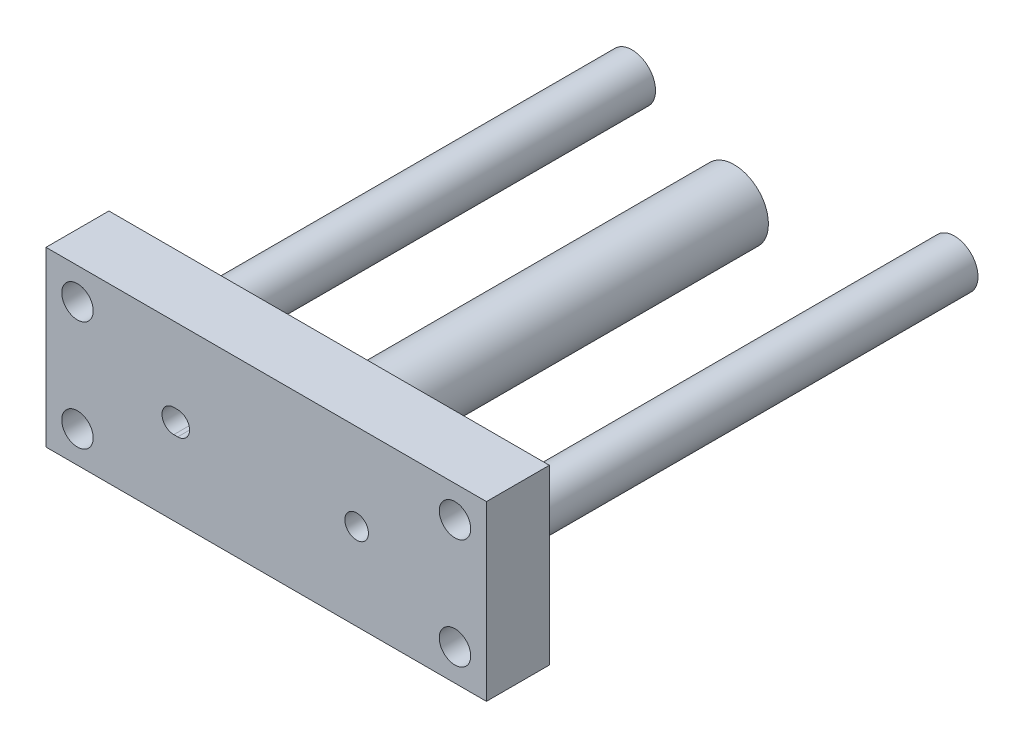
SolidWorks part; units mm, degrees
ref_plane "前视基准面" through (0, 0, 0) normal (0, 0, 1) x (1, 0, 0)
ref_plane "上视基准面" through (0, 0, 0) normal (0, 1, 0) x (1, 0, 0)
ref_plane "右视基准面" through (0, 0, 0) normal (1, 0, 0) x (0, 0, -1)
sketch "草图1" plane through (0, 0, 0) normal (0, 1, 0) x (1, 0, 0)
  line L0 (0, 0) -> (0, 54) construction
  line L1 (-29, 54) -> (29, 54)
  line L2 (-29, 54) -> (-29, 0)
  line L3 (-29, 0) -> (29, 0)
  line L4 (29, 54) -> (29, 0)
  line L5 (-11.5, 0) -> (-11.5, 54) construction
  line L6 (18, 54) -> (18, 0) construction
  line L7 (4.35, 0) -> (4.35, -5)
  line L8 (-29, -5) -> (29, -5)
  line L9 (-29, -5) -> (-29, -13)
  line L10 (-29, -13) -> (29, -13)
  line L11 (29, -5) -> (29, -13)
  line L12 (29, 0) -> (71, 0)
  circle A0 centre (18, 46.5) radius 2.5
  point P4 (29, 25)
  point P8 (0, 25)
  point P11 (-11.5, 5)
  point P12 (-11.5, 25)
  point P15 (18, 46.5)
  point P16 (18, 11)
  point P19 (29, 11)
  point P20 (29, 13.5)
  point P21 (29, 38.5)
  point P28 (0, 51)
  point P29 (0, 48)
  point P30 (-11.5, 15)
  point P31 (18, 54)
  point P33 (-11.5, 44)
  dimension "D2" = 38.5
  dimension "P" = 5
  dimension "D1" = 54
  dimension "B" = 58
  dimension "AC" = 29
  dimension "行程" = 25
  dimension "KB" = 23
  dimension "MB" = 5
  dimension "MC" = 20
  dimension "PB" = 18
  dimension "PD" = 11
  dimension "PF" = 7.5
  dimension "PC" = 11
  dimension "PE" = 13.5
  dimension "D3" = 8.7
  dimension "AD" = 8
  dimension "AB" = 13
  dimension "D4" = 67
  dimension "JA" = 3
  dimension "KA" = 6
  dimension "KC" = 15
  dimension "A" = 42
  dimension "LA" = 10
sketch "草图2" plane through (0, 0, 0) normal (0, 0, 1) x (1, 0, 0)
  line L0 (-29, 0) -> (0, 0) construction
  line L1 (-29, 13) -> (29, 13)
  line L2 (-29, 13) -> (-29, -13)
  line L3 (-29, -13) -> (-20.75, -13)
  line L4 (29, 13) -> (29, -13)
  line L5 (-29, 0) -> (29, 0) construction
  line L6 (0, 0) -> (0, 13) construction
  line L7 (-11.5, 13) -> (-11.5, -13) construction
  line L8 (-7.5, 13) -> (-7.5, 8.5)
  line L9 (-7.5, 8.5) -> (-9.25, 8.5)
  line L10 (-9.25, 8.5) -> (-9.25, -13)
  line L11 (29, 8) -> (24, 8)
  line L12 (-29, 0) -> (29, 0) construction
  line L13 (-11.75, 0) -> (-11.25, 0) construction
  line L14 (-11.75, 1.5) -> (-11.25, 1.5)
  line L15 (-11.75, -1.5) -> (-11.25, -1.5)
  line L16 (-9.25, -3) -> (-9, -3)
  line L17 (-2.25, -13) -> (-2.25, -12)
  line L18 (-9, -3) -> (-9, -13)
  line L19 (-4.5, -12) -> (-4.5, -13)
  line L20 (-16.25, -13) -> (-16.25, -11)
  line L21 (-16.25, -11) -> (-14.75, -11)
  line L22 (-14.75, -11) -> (-14.75, -7)
  line L23 (-14.75, -7) -> (-16.25, -7)
  line L24 (-22.25, -7) -> (-22.25, -11)
  line L25 (-22.25, -11) -> (-20.75, -11)
  line L26 (-20.75, -11) -> (-20.75, -13)
  line L27 (-23, 13) -> (-20.6, 10.6)
  line L28 (-20.6, 10.6) -> (-19.1, 10.6)
  line L29 (-19.1, 10.6) -> (-16.7, 13)
  line L36 (-20.75, -7) -> (-22.25, -7)
  line L37 (-20.75, -6.5) -> (-16.25, -6.5)
  line L38 (-20.75, -6.5) -> (-20.75, -7)
  line L39 (-16.25, -13) -> (29, -13)
  line L40 (-16.25, -6.5) -> (-16.25, -7)
  line L41 (-20.75, -13) -> (-16.25, -13) construction
  line L42 (-2.25, -12) -> (-1.25, -12)
  line L43 (-5.5, -10) -> (-1.25, -10)
  line L44 (-5.5, -10) -> (-5.5, -12)
  line L45 (-5.5, -12) -> (-4.5, -12)
  line L46 (-1.25, -10) -> (-1.25, -12)
  circle A0 centre (-20.5, 0) radius 3
  circle A1 centre (20.5, 0) radius 3
  circle A2 centre (-25, 9) radius 2
  circle A3 centre (-25, -9) radius 2
  circle A4 centre (11.5, 0) radius 1.5
  arc A5 (-11.75, 1.5) -> (-11.75, -1.5) centre (-11.75, 0) ccw
  arc A6 (-11.25, -1.5) -> (-11.25, 1.5) centre (-11.25, 0) ccw
  point P48 (-11.5, 0)
  point P52 (-18.5, -13)
  point P64 (-9.75, 0)
  point P65 (-13.25, 0)
  dimension "D1" = 1
  dimension "D" = 6
  dimension "D7" = 10.4
  dimension "L" = 4
  dimension "D10" = 2.4
  dimension "K" = 3
  dimension "C" = 26
  dimension "G" = 41
  dimension "U" = 7.5
  dimension "W" = 4
  dimension "V" = 4.5
  dimension "X" = 2
  dimension "Y" = 6.5
  dimension "S" = 37
  dimension "D2" = 1
  dimension "D3" = 2
  dimension "M" = 8
  dimension "MA" = 4.5
  dimension "N" = 4.5
  dimension "D4" = 2.25
  dimension "D5" = 2
  dimension "D6" = 135
  dimension "LC" = 18
  dimension "LB" = 50
  dimension "D8" = 2
  dimension "D9" = 5
  dimension "PA" = 8
  dimension "J" = 3.5
  dimension "R" = 5
  dimension "RA" = 10
sketch "草图3" plane through (0, 0, 0) normal (0, 0, 1) x (1, 0, 0)
  line L0 (0, 11) -> (0, 0) construction
  line L1 (-28, 11) -> (28, 11)
  line L2 (-28, 11) -> (-28, -11)
  line L3 (-28, -11) -> (28, -11)
  line L4 (28, 11) -> (28, -11)
  line L5 (-29, 0) -> (29, 0) construction
  line L6 (0, 0) -> (0, -11) construction
  line L7 (-29, 0) -> (29, 0) construction
  circle A0 centre (-24, 7) radius 2
  circle A1 centre (-25, 9) radius 2 construction
  dimension "BA" = 56
  dimension "CA" = 22
  dimension "LD" = 48
  dimension "LE" = 14
sketch "草图4" plane through (0, 0, 0) normal (0, 0, 1) x (1, 0, 0)
  line L0 (-14.75, -7) -> (-16.25, -7) construction
  line L1 (-14.75, -11) -> (-14.75, -7) construction
  line L2 (-16.25, -11) -> (-14.75, -11) construction
  line L3 (-16.25, -13) -> (-16.25, -11) construction
  line L4 (-16.25, -13) -> (29, -13) construction
  line L6 (-29, 13) -> (29, 13) construction
  line L7 (-29, 13) -> (-29, -13) construction
  line L8 (-29, -13) -> (-20.75, -13) construction
  line L9 (-20.75, -11) -> (-20.75, -13) construction
  line L10 (-22.25, -11) -> (-20.75, -11) construction
  line L11 (-22.25, -7) -> (-22.25, -11) construction
  line L12 (-20.75, -7) -> (-22.25, -7) construction
  line L13 (-20.75, -6.5) -> (-20.75, -7) construction
  line L14 (-20.75, -6.5) -> (-16.25, -6.5) construction
  line L15 (-16.25, -6.5) -> (-16.25, -7) construction
  line L26 (-23, 13) -> (-20.6, 10.6) construction
  line L27 (-20.6, 10.6) -> (-19.1, 10.6) construction
  line L28 (-19.1, 10.6) -> (-16.7, 13) construction
  line L29 (-14.75, -7) -> (-16.25, -7)
  line L30 (-14.75, -11) -> (-14.75, -7)
  line L31 (-16.25, -11) -> (-14.75, -11)
  line L32 (-16.25, -13) -> (-16.25, -11)
  line L33 (-16.25, -13) -> (0, -13)
  line L35 (-29, 13) -> (-23, 13)
  line L36 (-29, 13) -> (-29, -13)
  line L37 (-29, -13) -> (-20.75, -13)
  line L38 (-20.75, -11) -> (-20.75, -13)
  line L39 (-22.25, -11) -> (-20.75, -11)
  line L40 (-22.25, -7) -> (-22.25, -11)
  line L41 (-20.75, -7) -> (-22.25, -7)
  line L42 (-20.75, -6.5) -> (-20.75, -7)
  line L43 (-20.75, -6.5) -> (-16.25, -6.5)
  line L44 (-16.25, -6.5) -> (-16.25, -7)
  line L45 (0, 13) -> (0, -13)
  line L52 (-16.7, 13) -> (0, 13)
  line L55 (-23, 13) -> (-20.6, 10.6)
  line L56 (-20.6, 10.6) -> (-19.1, 10.6)
  line L57 (-19.1, 10.6) -> (-16.7, 13)
  circle A4 centre (-20.5, 0) radius 3 construction
  circle A5 centre (-20.5, 0) radius 3
extrude "凸台-拉伸1" add sketch "草图4" against normal up to vertex (54 mm away) up to point (0, 0, -54)
sketch "草图5" plane through (0, 0, 0) normal (0, 0, 1) x (1, 0, 0)
  line L0 (-5.5, -12) -> (-4.5, -12) construction
  line L1 (-4.5, -12) -> (-4.5, -13) construction
  line L2 (-5.5, -10) -> (-5.5, -12) construction
  line L3 (-5.5, -10) -> (-1.25, -10) construction
  line L4 (-1.25, -10) -> (-1.25, -12) construction
  line L5 (-2.25, -12) -> (-1.25, -12) construction
  line L6 (-2.25, -13) -> (-2.25, -12) construction
  line L7 (-5.5, -12) -> (-4.5, -12)
  line L8 (-4.5, -12) -> (-4.5, -13)
  line L9 (-5.5, -10) -> (-5.5, -12)
  line L10 (-5.5, -10) -> (-1.25, -10)
  line L11 (-1.25, -10) -> (-1.25, -12)
  line L12 (-2.25, -12) -> (-1.25, -12)
  line L13 (-2.25, -13) -> (-2.25, -12)
  line L14 (-4.5, -13) -> (-2.25, -13)
extrude "切除-拉伸1" cut sketch "草图5" against normal through all
mirror "镜向1" about plane through (0, 0, 0) normal (0, 1, 0) of "切除-拉伸1"
sketch "草图6" plane through (0, 13, 0) normal (0, 1, 0) x (-1, 0, 0)
  circle A0 centre (11.5, -25) radius 4
  circle A1 centre (11.5, -5) radius 4
  point P6 (7.5, -5)
extrude "切除-拉伸2" cut sketch "草图6" against normal up to vertex (4.5 mm away) up to point (-7.5, 8.5, 0)
sketch "草图7" plane through (0, 8.5, 0) normal (0, 1, 0) x (1, 0, 0)
  circle A0 centre (-11.5, 25) radius 2.25
  circle A1 centre (-11.5, 5) radius 2.25
  point P6 (-9.25, 25)
extrude "切除-拉伸3" cut sketch "草图7" against normal up to vertex (21.5 mm away) up to point (-9.25, -13, 0)
mirror "镜向2" about plane through (0, 0, 0) normal (1, 0, 0) of bodies 105
sketch "草图8" plane through (0, 0, 0) normal (0, 0, 1) x (1, 0, 0)
  line L0 (16.7, 13) -> (23, 13)
  line L1 (23, 13) -> (20.6, 10.6)
  line L2 (20.6, 10.6) -> (19.1, 10.6)
  line L3 (19.1, 10.6) -> (16.7, 13)
extrude "凸台-拉伸2" add sketch "草图8" against normal up to surface (54 mm away) up to face at (-17.5, 0, -54)
sketch "草图9" plane through (0, 13, 0) normal (0, 1, 0) x (1, 0, 0)
  circle A0 centre (18, 46.5) radius 2.5
  circle A1 centre (18, 11) radius 2.5
  circle A2 centre (18, 46.5) radius 2.5 construction
extrude "切除-拉伸4" cut sketch "草图9" against normal blind 5
sketch "草图10" plane through (29, 0, 0) normal (1, 0, 0) x (0, 0, -1)
  circle A0 centre (11, 8) radius 2.5
  circle A1 centre (38.5, 8) radius 2.5
  dimension "D1" = 5
extrude "切除-拉伸5" cut sketch "草图10" against normal up to vertex (5 mm away) up to point (24, 8, 0)
sketch "草图11" plane through (0, 0, 0) normal (0, 0, 1) x (1, 0, 0)
  line L0 (-29, 0) -> (29, 0) construction
  circle A0 centre (0, 0) radius 4.35
extrude "切除-拉伸6" cut sketch "草图11" against normal up to vertex (46.5 mm away) up to point (18, 0, -46.5)
sketch "草图12" plane through (0, 0, -54) normal (0, 0, -1) x (-1, 0, 0)
  line L0 (11.75, 1.5) -> (11.25, 1.5) construction
  line L1 (11.75, -1.5) -> (11.25, -1.5) construction
  line L2 (11.75, 1.5) -> (11.25, 1.5)
  line L3 (11.75, -1.5) -> (11.25, -1.5)
  circle A0 centre (-11.5, 0) radius 1.5 construction
  arc A1 (11.75, -1.5) -> (11.75, 1.5) centre (11.75, 0) ccw construction
  arc A2 (11.25, 1.5) -> (11.25, -1.5) centre (11.25, 0) ccw construction
  circle A3 centre (-11.5, 0) radius 1.5
  arc A4 (11.75, -1.5) -> (11.75, 1.5) centre (11.75, 0) ccw
  arc A5 (11.25, 1.5) -> (11.25, -1.5) centre (11.25, 0) ccw
extrude "切除-拉伸7" cut sketch "草图12" against normal up to vertex (3 mm away) up to point (0, 0, -51)
sketch "草图13" plane through (0, 0, -51) normal (0, 0, -1) x (-1, 0, 0)
  line L0 (11.5, 13) -> (11.5, -13) construction
  circle A0 centre (11.5, 0) radius 1.5
  circle A2 centre (-11.5, 0) radius 1.5
  circle A3 centre (-11.5, 0) radius 1.5
  dimension "D1" = 0
extrude "凸台-拉伸4" add sketch "草图13" against normal up to vertex (3 mm away) up to point (0, 0, -48)
sketch "草图14" plane through (0, -13, 0) normal (0, -1, 0) x (1, 0, 0)
  circle A0 centre (-11.5, -15) radius 1.5
  circle A1 centre (11.5, -15) radius 1.5
  dimension "D1" = 3
extrude "切除-拉伸8" cut sketch "草图14" against normal blind 6
sketch "草图15" plane through (0, -13, 0) normal (0, -1, 0) x (1, 0, 0)
  line L0 (-11.75, -15) -> (-11.25, -15) construction
  line L1 (-11.75, -13.5) -> (-11.25, -13.5)
  line L2 (-11.75, -16.5) -> (-11.25, -16.5)
  arc A0 (-11.75, -13.5) -> (-11.75, -16.5) centre (-11.75, -15) ccw
  arc A1 (-11.25, -16.5) -> (-11.25, -13.5) centre (-11.25, -15) ccw
  point P2 (-11.5, -15)
  point P7 (-9.75, -15)
  point P8 (-13.25, -15)
  dimension "D1" = 3.5
  dimension "D2" = 1.5
extrude "切除-拉伸9" cut sketch "草图15" against normal blind 3
sketch "草图16" plane through (0, 0, 0) normal (0, 0, 1) x (1, 0, 0)
  line L0 (-28, 11) -> (28, 11) construction
  line L1 (28, 11) -> (28, -11) construction
  line L2 (-28, -11) -> (28, -11) construction
  line L3 (-28, 11) -> (-28, -11) construction
  line L4 (-28, 11) -> (28, 11)
  line L5 (28, 11) -> (28, -11)
  line L6 (-28, -11) -> (28, -11)
  line L7 (-28, 11) -> (-28, -11)
extrude "凸台-拉伸5" add sketch "草图16" along normal up to vertex (13 mm away) from vertex at 5 separate body starting at point (29, 0, 5)
sketch "草图18" plane through (0, 0, 13) normal (0, 0, 1) x (1, 0, 0)
  circle A0 centre (20.5, 0) radius 3 construction
  circle A1 centre (-20.5, 0) radius 3 construction
  circle A2 centre (20.5, 0) radius 3
  circle A3 centre (-20.5, 0) radius 3
extrude "凸台-拉伸6" add sketch "草图18" against normal up to vertex (67 mm away) up to point (18, 0, -54)
sketch "草图19" plane through (0, 0, 13) normal (0, 0, 1) x (1, 0, 0)
  circle A0 centre (0, 0) radius 4.35
extrude "凸台-拉伸7" add sketch "草图19" against normal up to vertex (59.5 mm away) up to point (18, 0, -46.5)
sketch "草图20" plane through (0, 0, 13) normal (0, 0, 1) x (1, 0, 0)
  circle A0 centre (-24, 7) radius 2 construction
  circle A1 centre (-24, 7) radius 2
extrude "切除-拉伸10" cut sketch "草图20" against normal up to vertex (8 mm away) up to point (-29, 0, 5)
mirror "镜向3" about plane through (0, 0, 0) normal (0, 1, 0) of "切除-拉伸10"
mirror "镜向4" about plane through (0, 0, 0) normal (1, 0, 0) of "镜向3", "切除-拉伸10"
sketch "草图21" plane through (0, 0, 13) normal (0, 0, 1) x (1, 0, 0)
  line L0 (-11.75, 1.5) -> (-11.25, 1.5) construction
  line L1 (-11.75, -1.5) -> (-11.25, -1.5) construction
  line L2 (-11.75, 1.5) -> (-11.25, 1.5)
  line L3 (-11.75, -1.5) -> (-11.25, -1.5)
  circle A0 centre (11.5, 0) radius 1.5 construction
  arc A1 (-11.25, -1.5) -> (-11.25, 1.5) centre (-11.25, 0) ccw construction
  arc A2 (-11.75, 1.5) -> (-11.75, -1.5) centre (-11.75, 0) ccw construction
  circle A3 centre (11.5, 0) radius 1.5
  arc A4 (-11.25, -1.5) -> (-11.25, 1.5) centre (-11.25, 0) ccw
  arc A5 (-11.75, 1.5) -> (-11.75, -1.5) centre (-11.75, 0) ccw
extrude "切除-拉伸11" cut sketch "草图21" against normal blind 3
sketch "草图22" plane through (0, 0, 10) normal (0, 0, 1) x (1, 0, 0)
  circle A0 centre (-11.5, 0) radius 1.5
  circle A1 centre (11.5, 0) radius 1.5
  circle A2 centre (11.5, 0) radius 1.5
  dimension "D1" = 0
extrude "切除-拉伸12" cut sketch "草图22" against normal blind 3
delete or keep bodies "实体-删除1" type delete bodies bodies 115
sketch "草图23" plane through (0, 0, 0) normal (0, 1, 0) x (1, 0, 0)
  point P0 (0, 0)
